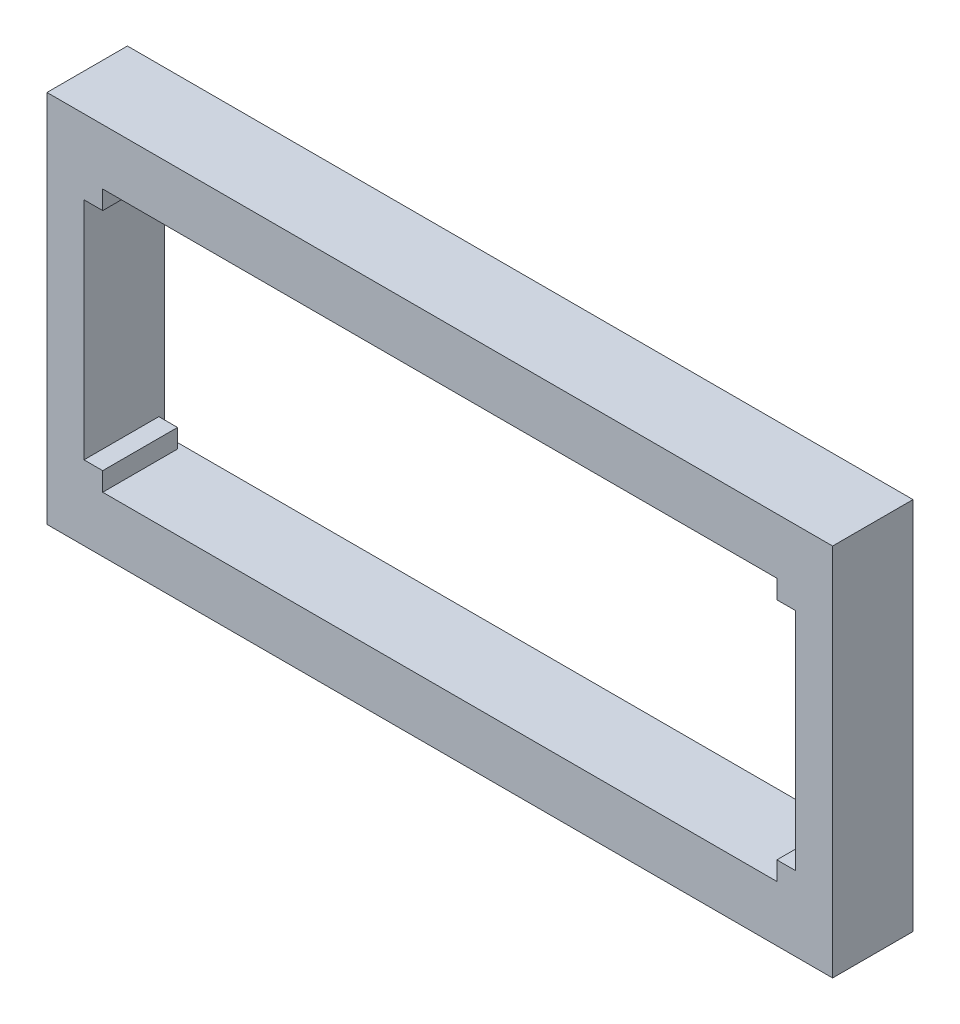
SolidWorks part; units mm, degrees
ref_plane "Front Plane" through (0, 0, 0) normal (0, 0, 1) x (1, 0, 0)
ref_plane "Top Plane" through (0, 0, 0) normal (0, 1, 0) x (1, 0, 0)
ref_plane "Right Plane" through (0, 0, 0) normal (1, 0, 0) x (0, 0, -1)
sketch "Sketch1" plane through (0, 0, 0) normal (0, 0, 1) x (1, 0, 0)
  line L1 (0, 0) -> (190.2, 0)
  line L2 (0, 0) -> (0, 70.2)
  line L3 (0, 70.2) -> (190.2, 70.2)
  line L4 (190.2, 0) -> (190.2, 70.2)
  line L5 (-9.9, 85.1) -> (200.1, 85.1)
  line L6 (-9.9, 85.1) -> (-9.9, -14.9)
  line L7 (-9.9, -14.9) -> (200.1, -14.9)
  line L8 (200.1, 85.1) -> (200.1, -14.9)
  point P9 (95.1, 70.2)
  point P10 (95.1, 85.1)
  point P11 (0, 35.1)
  point P12 (-9.9, 35.1)
  dimension "D1" = 190.2
  dimension "D2" = 70.2
  dimension "D3" = 210
  dimension "D4" = 100
extrude "Boss-Extrude1" add sketch "Sketch1" along normal blind 1.5
sketch "Sketch2" plane through (0, 0, 1.5) normal (0, 0, 1) x (1, 0, 0)
  line L1 (-9.9, 85.1) -> (200.1, 85.1)
  line L2 (-9.9, 85.1) -> (-9.9, -14.9)
  line L3 (-9.9, -14.9) -> (200.1, -14.9)
  line L4 (200.1, 85.1) -> (200.1, -14.9)
  line L5 (0, 70.2) -> (190.2, 70.2)
  line L6 (0, 70.2) -> (0, 0)
  line L7 (0, 0) -> (190.2, 0)
  line L8 (190.2, 70.2) -> (190.2, 0)
  line L9 (0, 70.2) -> (5, 70.2)
  line L10 (0, 70.2) -> (0, 65.2)
  line L11 (0, 65.2) -> (5, 65.2)
  line L12 (5, 70.2) -> (5, 65.2)
  line L13 (0, 0) -> (5, 0)
  line L14 (0, 0) -> (0, 5)
  line L15 (0, 5) -> (5, 5)
  line L16 (5, 0) -> (5, 5)
  line L17 (190.2, 70.2) -> (185.2, 70.2)
  line L18 (190.2, 70.2) -> (190.2, 65.2)
  line L19 (190.2, 65.2) -> (185.2, 65.2)
  line L20 (185.2, 70.2) -> (185.2, 65.2)
  line L21 (190.2, 0) -> (185.2, 0)
  line L22 (190.2, 0) -> (190.2, 5)
  line L23 (190.2, 5) -> (185.2, 5)
  line L24 (185.2, 0) -> (185.2, 5)
  line M25 (-9.9, 85.1) -> (-9.9, -14.9)
  line M26 (-9.9, -14.9) -> (200.1, -14.9)
  line M27 (200.1, -14.9) -> (200.1, 85.1)
  line M28 (200.1, 85.1) -> (-9.9, 85.1)
  line M29 (190.2, 0) -> (0, 0)
  line M30 (0, 0) -> (0, 70.2)
  line M31 (0, 70.2) -> (190.2, 70.2)
  line M32 (190.2, 70.2) -> (190.2, 0)
  dimension "D1" = 5
extrude "Boss-Extrude2" add sketch "Sketch2" along normal blind 20 contours L8 L7 L6 L5 M28 M25 M26 M27 M32 M29 M30 M31 | L10 L11 L12 L9 | L14 L15 L16 L13 | L17 L20 L19 L18 | L22 L23 L24 L21
